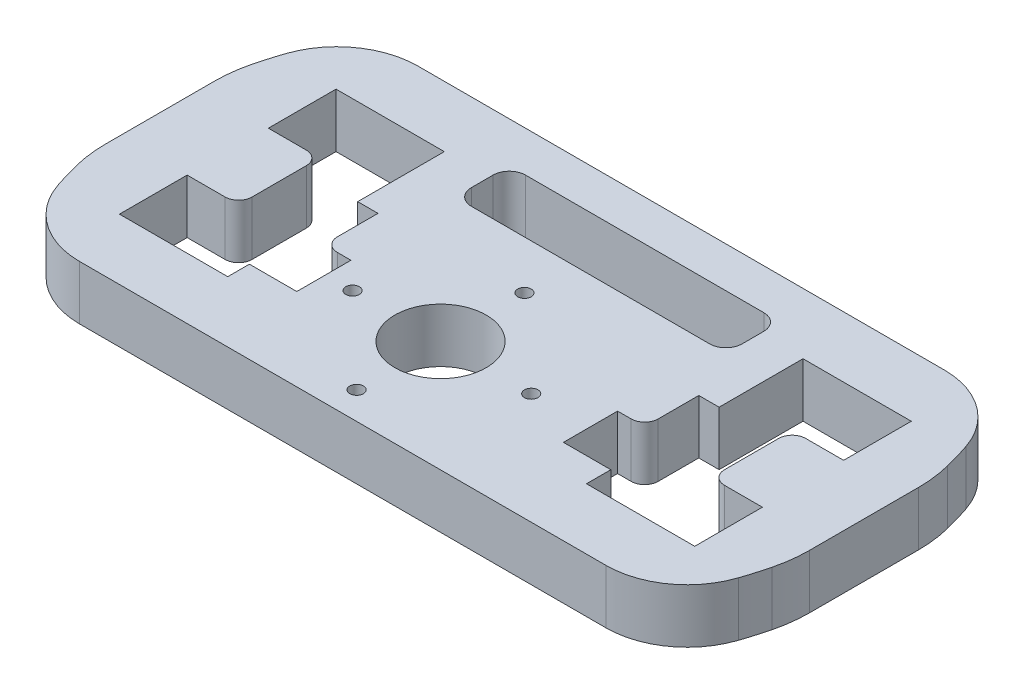
SolidWorks part; units mm, degrees
ref_plane "Piano frontale" through (0, 0, 0) normal (0, 0, 1) x (1, 0, 0)
ref_plane "Piano superiore" through (0, 0, 0) normal (0, 1, 0) x (1, 0, 0)
ref_plane "Piano destro" through (0, 0, 0) normal (1, 0, 0) x (0, 0, -1)
sketch "Schizzo1" plane through (0, 0, 0) normal (0, 1, 0) x (1, 0, 0)
  line L0 (5, 20.5) -> (13, 20.5)
  line L1 (0, 0) -> (52, 0)
  line L2 (0, 0) -> (0, 25)
  line L3 (0, 25) -> (52, 25)
  line L4 (52, 0) -> (52, 25)
  line L5 (13, 20.5) -> (13, 14.1)
  line L6 (13, 14.1) -> (14.5, 14.1)
  line L7 (17.5, 22) -> (35.1, 22)
  line L8 (16.3, 20.8) -> (16.3, 19.2)
  line L9 (17.5, 18) -> (35.1, 18)
  line L10 (36.3, 20.8) -> (36.3, 19.2)
  line L11 (14.5, 14.1) -> (14.5, 11.1)
  line L12 (15.5, 10.1) -> (16.5, 10.1)
  line L13 (16.5, 10.1) -> (16.5, 6.1)
  line L14 (16.5, 6.1) -> (13, 6.1)
  line L15 (13, 6.1) -> (13, 4.5)
  line L16 (5, 4.5) -> (13, 4.5)
  line L17 (5, 4.5) -> (5, 9.5)
  line L18 (5, 9.5) -> (7.8, 9.5)
  line L19 (8.8, 10.5) -> (8.8, 14.5)
  line L20 (7.8, 15.5) -> (5, 15.5)
  line L21 (5, 15.5) -> (5, 20.5)
  line L22 (25, 25) -> (25, 0)
  line L23 (39.5, 6.3) -> (39.5, 4.5)
  line L24 (36, 6.3) -> (39.5, 6.3)
  line L25 (36, 10.3) -> (36, 6.3)
  line L26 (37, 10.3) -> (36, 10.3)
  line L27 (38, 14.3) -> (38, 11.3)
  line L28 (39.5, 14.3) -> (38, 14.3)
  line L29 (39.5, 20.5) -> (39.5, 14.3)
  line L30 (47.5, 20.5) -> (39.5, 20.5)
  line L31 (47.5, 15.5) -> (47.5, 20.5)
  line L32 (44.7, 15.5) -> (47.5, 15.5)
  line L33 (43.7, 10.5) -> (43.7, 14.5)
  line L34 (47.5, 9.5) -> (44.7, 9.5)
  line L35 (47.5, 4.5) -> (47.5, 9.5)
  line L36 (47.5, 4.5) -> (39.5, 4.5)
  circle A0 centre (25, 8.22) radius 3.375
  arc A1 (15.5, 10.1) -> (14.5, 11.1) centre (15.5, 11.1) cw
  arc A2 (38, 11.3) -> (37, 10.3) centre (37, 11.3) cw
  arc A3 (44.7, 9.5) -> (43.7, 10.5) centre (44.7, 10.5) cw
  arc A4 (8.8, 10.5) -> (7.8, 9.5) centre (7.8, 10.5) cw
  arc A5 (8.8, 14.5) -> (7.8, 15.5) centre (7.8, 14.5) ccw
  arc A6 (44.7, 15.5) -> (43.7, 14.5) centre (44.7, 14.5) ccw
  circle A7 centre (26, 12.5) radius 26.5
  arc A8 (16.3, 19.2) -> (17.5, 18) centre (17.5, 19.2) ccw
  arc A9 (17.5, 22) -> (16.3, 20.8) centre (17.5, 20.8) ccw
  arc A10 (36.3, 20.8) -> (35.1, 22) centre (35.1, 20.8) ccw
  arc A11 (36.3, 19.2) -> (35.1, 18) centre (35.1, 19.2) cw
  point P0 (0, 0)
  point P6 (0, 5.6156)
  point P33 (16.3, 18)
  point P36 (16.3, 22)
  point P39 (36.3, 22)
  point P42 (36.3, 18)
  point P46 (8.8, 12.5)
  point P47 (0, 12.5)
  point P64 (14.5, 10.1)
  point P67 (38, 10.3)
  point P70 (43.7, 9.5)
  point P73 (8.8, 9.5)
  point P76 (8.8, 15.5)
  point P79 (43.7, 15.5)
  dimension "D3" = 6.75
  dimension "D19" = 1
  dimension "D20" = 1
  dimension "D21" = 1
  dimension "D22" = 1
  dimension "D39" = 26
  dimension "D40" = 53
  dimension "D42" = 1.2
  dimension "D1" = 52
  dimension "D2" = 25
  dimension "D4" = 8.22
  dimension "D5" = 20
  dimension "D6" = 4
  dimension "D7" = 3
  dimension "D8" = 6
  dimension "D9" = 5
  dimension "D10" = 5
  dimension "D11" = 3.8
  dimension "D12" = 8
  dimension "D13" = 1.5
  dimension "D14" = 2
  dimension "D15" = 4
  dimension "D16" = 6.4
  dimension "D17" = 4
  dimension "D18" = 20
  dimension "D23" = 4
  dimension "D24" = 8
  dimension "D25" = 6.2
  dimension "D26" = 3.5
  dimension "D27" = 2
  dimension "D28" = 1.5
  dimension "D29" = 4
  dimension "D30" = 5
  dimension "D31" = 5
  dimension "D32" = 8
  dimension "D33" = 4
  dimension "D34" = 2.8
  dimension "D35" = 22.5
  dimension "D36" = 4.5
  dimension "D37" = 25
  dimension "D38" = 11.3
  dimension "D41" = 12.5
extrude "Estrusione-Estrusione1" add sketch "Schizzo1" along normal blind 4 contours A0 L22 L9 L8 L7 L3 L2 L1 L19 A5 L20 L21 L0 L5 L6 L11 A1 L12 L13 L14 L15 L16 L17 L18 A4 | A0 L22 L1 L4 L3 L7 L10 L9 L32 A6 L33 A3 L34 L35 L36 L23 L24 L25 L26 A2 L27 L28 L29 L30 L31
fillet "Raccordo1" radius 6 1 edges at (2.6334, 2, -25)
fillet "Raccordo4" radius 6 1 edges at (2.6334, 2, 0)
fillet "Raccordo5" radius 6 1 edges at (49.3666, 2, -25)
fillet "Raccordo6" radius 6 1 edges at (49.3666, 2, 0)
fillet "Raccordo8" radius 10 1 edges at (0, 2, -7.3765)
fillet "Raccordo9" radius 10 1 edges at (0, 2, -17.6235)
fillet "Raccordo10" radius 10 1 edges at (52, 2, -17.6235)
fillet "Raccordo11" radius 10 1 edges at (52, 2, -7.3765)
sketch "Schizzo2" plane through (0, 0, 0) normal (0, -1, 0) x (1, 0, 0)
  circle A0 centre (25, -14.42) radius 0.5
  circle A1 centre (31.7, -8.22) radius 0.5
  circle A2 centre (18.5, -8.22) radius 0.5
  circle A3 centre (25, -2.02) radius 0.5
  dimension "D1" = 1
  dimension "D2" = 1
  dimension "D3" = 1
  dimension "D4" = 1
  dimension "D5" = 6.7
  dimension "D6" = 6.5
  dimension "D7" = 6.2
  dimension "D8" = 6.2
extrude "Taglio-Estrusione1" cut sketch "Schizzo2" against normal through all
